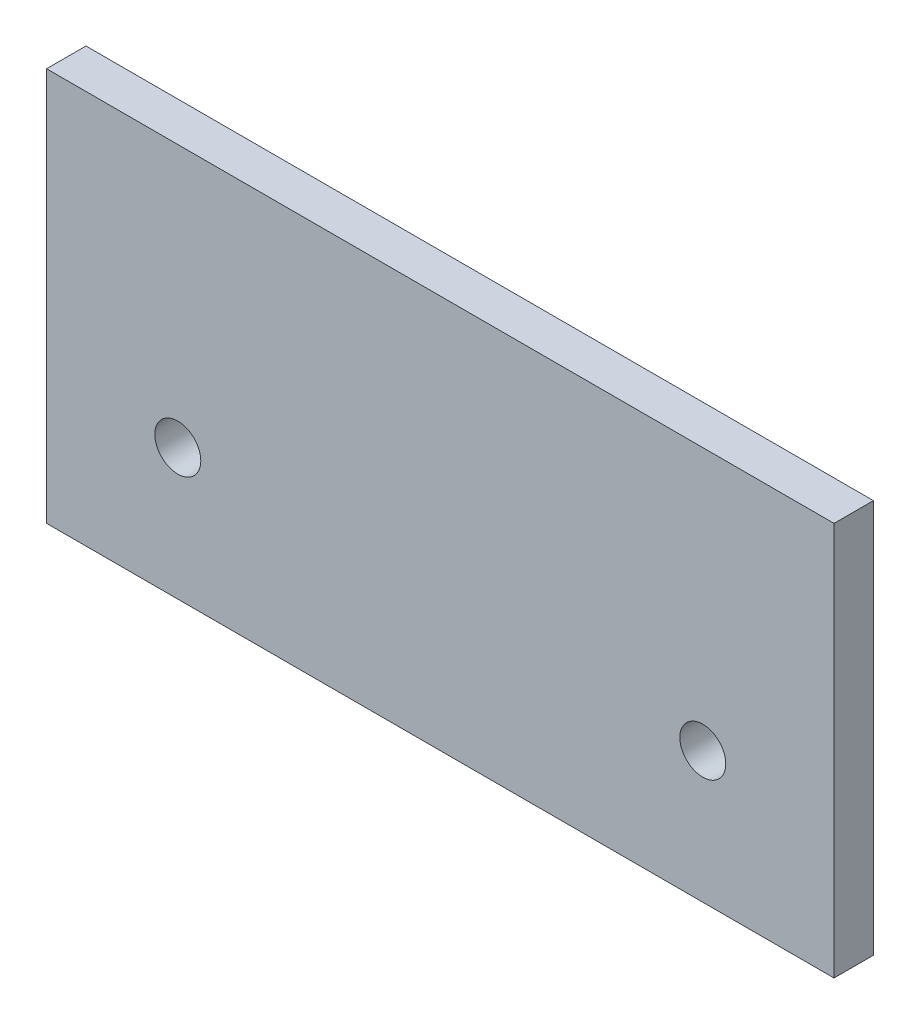
SolidWorks part; units mm, degrees
ref_plane "前基準面" through (0, 0, 0) normal (0, 0, 1) x (1, 0, 0)
ref_plane "上基準面" through (0, 0, 0) normal (0, 1, 0) x (1, 0, 0)
ref_plane "右基準面" through (0, 0, 0) normal (1, 0, 0) x (0, 0, -1)
sketch "草圖1" plane through (0, 0, 0) normal (0, 0, 1) x (1, 0, 0)
  line L0 (10, 0) -> (10, -10) construction
  line L1 (-50, 20) -> (10, 20)
  line L2 (-50, 20) -> (-50, -10)
  line L3 (-50, -10) -> (10, -10)
  line L4 (10, 20) -> (10, -10)
  line L5 (10, 0) -> (0, 0) construction
  dimension "D1" = 60
  dimension "D2" = 30
  dimension "D3" = 10
  dimension "D4" = 10
extrude "伸長1" add sketch "草圖1" along normal blind 3
sketch "草圖2" plane through (0, 0, 3) normal (0, 0, 1) x (1, 0, 0)
  line L1 (0, 0) -> (-40, 0) construction
  circle A0 centre (-40, 0) radius 1.75
  circle A1 centre (0, 0) radius 1.75
  dimension "D3" = 3.5
  dimension "D1" = 40
extrude "伸長2" cut sketch "草圖2" against normal through all
